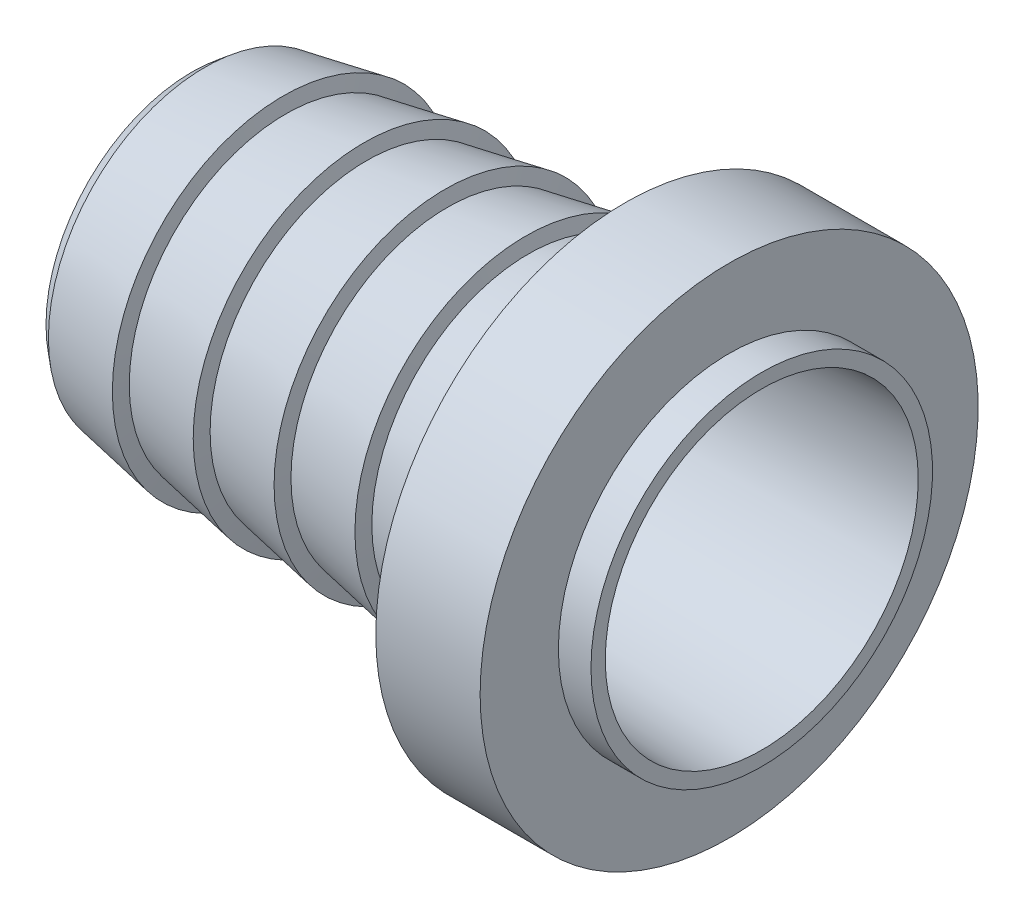
SolidWorks part; units mm, degrees
ref_plane "Front Plane" through (0, 0, 0) normal (0, 0, 1) x (1, 0, 0)
ref_plane "Top Plane" through (0, 0, 0) normal (0, 1, 0) x (1, 0, 0)
ref_plane "Right Plane" through (0, 0, 0) normal (1, 0, 0) x (0, 0, -1)
sketch "Sketch1" plane through (0, 0, 0) normal (0, 1, 0) x (1, 0, 0)
  line L0 (0, 0) -> (61.4833, 0) construction
  line L2 (-5.2397, 13.0954) -> (53.9675, 13.0954) construction
  line L3 (0, 10.0954) -> (0, 11.1836)
  line L4 (0, 11.1836) -> (1, 12)
  line L5 (1, 12) -> (7, 13.0954)
  line L6 (1, 12) -> (43.7, 12) construction
  line L7 (7, 13.0954) -> (7.2, 12)
  line L14 (7.2, 12) -> (13.2, 13.0954)
  line L22 (13.2, 13.0954) -> (13.4, 12)
  line L23 (13.4, 12) -> (19.4, 13.0954)
  line L24 (19.4, 13.0954) -> (19.6, 12)
  line L25 (19.6, 12) -> (25.6, 13.0954)
  line L26 (25.6, 13.0954) -> (25.8, 12)
  line L27 (25.8, 12) -> (31.8, 13.0954)
  line L28 (31.8, 13.0954) -> (33.2, 13.0954)
  line L29 (31.8, 13.0954) -> (32, 12) [skipped]
  line L30 (33.2, 13.0954) -> (33.2, 19.0954)
  line L31 (33.2, 19.0954) -> (41.2, 19.0954)
  line L39 (0, 12) -> (43.7, 12) construction
  line L40 (-5.2397, 13.0954) -> (43.7, 13.0954) construction
  line L43 (41.2, 19.0954) -> (41.2, 13.0954)
  line L44 (41.2, 13.0954) -> (43.7, 13.0954)
  line L45 (0, 10.0954) -> (43.7, 12)
  line L46 (43.7, 12) -> (43.7, 13.0954)
  point P17 (0, 0)
  point P21 (53.9675, 11.9046)
  dimension "D2" = 2.5
  dimension "D3" = 12
  dimension "D5" = 6
  dimension "D6" = 1
  dimension "D7" = 0.2
  dimension "D9" = 6
  dimension "D10" = 1.4
  dimension "D11" = 8
  dimension "D8" = 5
revolve "Revolve2" add sketch "Sketch1" angle 360 about L0
